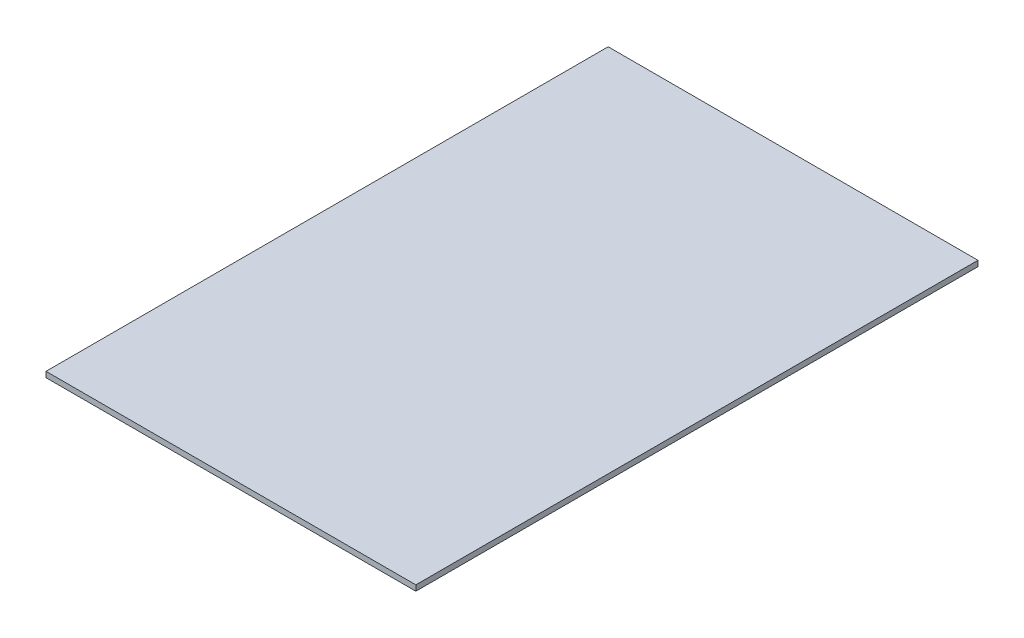
SolidWorks part; units mm, degrees
ref_plane "Front Plane" through (0, 0, 0) normal (0, 0, 1) x (1, 0, 0)
ref_plane "Top Plane" through (0, 0, 0) normal (0, 1, 0) x (1, 0, 0)
ref_plane "Right Plane" through (0, 0, 0) normal (1, 0, 0) x (0, 0, -1)
sketch "Sketch1" plane through (0, 0, 0) normal (0, 1, 0) x (1, 0, 0)
  line L1 (0, 0) -> (200, 0)
  line L2 (0, 0) -> (0, -304)
  line L3 (0, -304) -> (200, -304)
  line L4 (200, 0) -> (200, -304)
  dimension "D1" = 304
  dimension "D2" = 200
extrude "Boss-Extrude1" add sketch "Sketch1" along normal blind 3
